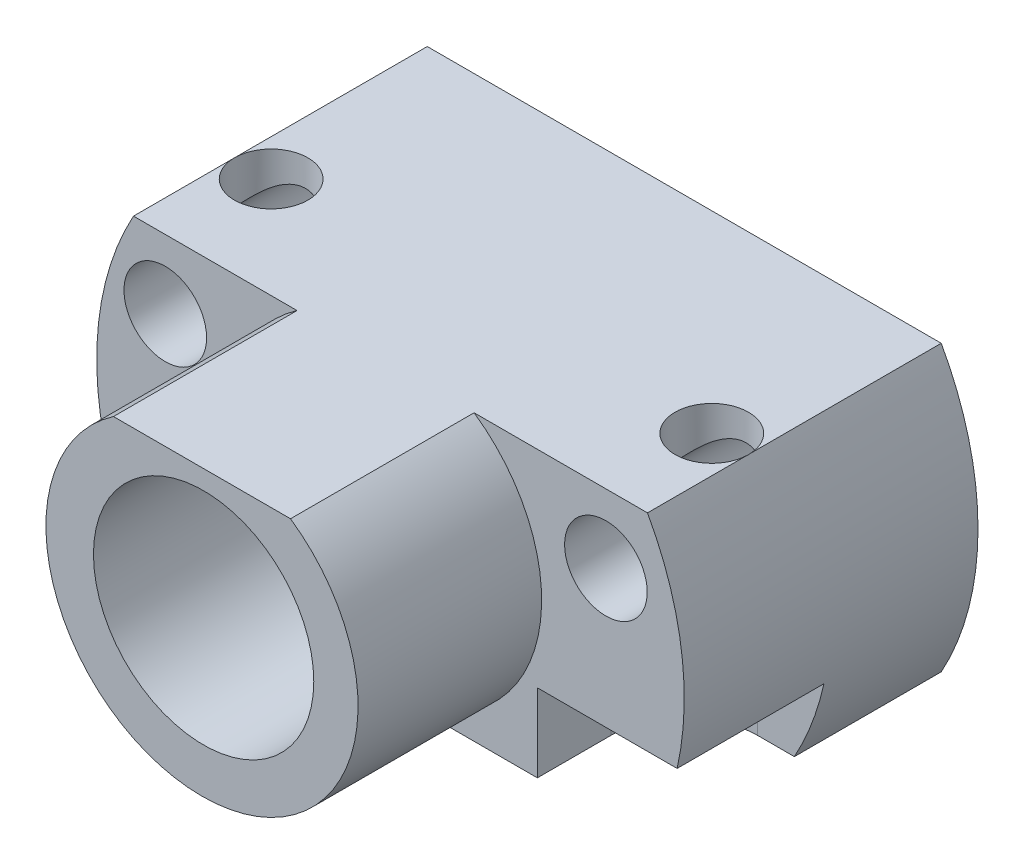
SolidWorks part; units mm, degrees
ref_plane "Plan de face" through (0, 0, 0) normal (0, 0, 1) x (1, 0, 0)
ref_plane "Plan de dessus" through (0, 0, 0) normal (0, 1, 0) x (1, 0, 0)
ref_plane "Plan de droite" through (0, 0, 0) normal (1, 0, 0) x (0, 0, -1)
sketch "Esquisse1" plane through (0, 0, 0) normal (0, 0, 1) x (1, 0, 0)
  line L1 (-27.4613, 12.1711) -> (28.5298, 12.1711)
  line L3 (-27.4613, -18.8289) -> (28.5298, -18.8289)
  arc A0 (-27.4613, 12.1711) -> (-27.4613, -18.8289) centre (0.5343, -3.3289) ccw
  arc A1 (28.5298, -18.8289) -> (28.5298, 12.1711) centre (0.5343, -3.3289) ccw
  dimension "D1" = 31
extrude "Boss.-Extru.1" add sketch "Esquisse1" along normal blind 32 contours A0 L3 A1 L1
sketch "Esquisse2" plane through (0, -18.8289, 0) normal (0, -1, 0) x (1, 0, 0)
  line L0 (0.5343, 32) -> (0.5343, -62.2542) construction
  line L1 (-27.4613, 0) -> (28.5298, 0) construction
  circle A0 centre (24.5343, 21) radius 4
  circle A1 centre (-23.4657, 21) radius 4
  dimension "D1" = 24
  dimension "D3" = 8
  dimension "D2" = 21
extrude "Enlèv. mat.-Extru.1" cut sketch "Esquisse2" against normal blind 32
sketch "Esquisse3" plane through (0, 0, 0) normal (0, 0, 1) x (1, 0, 0)
  line L0 (-27.4613, 12.1711) -> (28.5298, 12.1711) construction
  line L1 (0, 0) -> (0, 50000) construction
  circle A0 centre (-24, 4.6711) radius 4.5
  circle A1 centre (24, 4.6711) radius 4.5
  dimension "D1" = 7.5
  dimension "D2" = 24
extrude "Enlèv. mat.-Extru.3" cut sketch "Esquisse3" along normal blind 42
sketch "Esquisse4" [suppressed] plane through (0, 0, 0) normal (0, 1, 0) x (1, 0, 0)
  line L0 (16.5343, -32) -> (16.5343, -24)
  line L1 (-27.4613, -32) -> (28.5298, -32) construction
  line L2 (32.5343, -32) -> (32.5343, 0) construction
  line L3 (32.5343, -16) -> (24.5343, -16)
  line L4 (28.5298, -32) -> (32.5343, -32) construction
  line L5 (0.5343, -32) -> (0.5343, 49968) construction
  line L6 (-31.4657, -16) -> (-23.4657, -16)
  line L7 (-15.4657, -32) -> (-15.4657, -24)
  line L8 (32.5343, -16) -> (32.5343, -32)
  line L9 (32.5343, -32) -> (16.5343, -32)
  line L10 (-15.4657, -32) -> (-31.4657, -32)
  line L11 (-31.4657, -32) -> (-31.4657, -16)
  arc A0 (16.5343, -24) -> (24.5343, -16) centre (24.5343, -24) cw
  arc A1 (-15.4657, -24) -> (-23.4657, -16) centre (-23.4657, -24) ccw
  point P13 (0.5343, -32)
  point P19 (0, 0)
  point P24 (-15.4657, -24)
  dimension "D1" = 8
  dimension "D2" = 16
  dimension "D3" = 16
sketch "Esquisse5" plane through (0, -18.8289, 0) normal (0, -1, 0) x (1, 0, 0)
  line L0 (-15.4657, 32) -> (-15.4657, 24)
  line L1 (-27.4613, 32) -> (28.5298, 32) construction
  line L2 (-23.4657, 16) -> (-31.4657, 16)
  line L3 (-31.4657, 32) -> (-31.4657, 0) construction
  line L4 (-31.4657, 16) -> (-31.4657, 32)
  line L5 (-31.4657, 32) -> (-15.4657, 32)
  line L6 (0.5343, 32) -> (0.5343, -49968) construction
  line L7 (24.5343, 16) -> (32.5343, 16)
  line L8 (32.5343, 16) -> (32.5343, 32)
  line L9 (32.5343, 32) -> (16.5343, 32)
  line L10 (16.5343, 32) -> (16.5343, 24)
  arc A0 (-15.4657, 24) -> (-23.4657, 16) centre (-23.4657, 24) cw
  arc A1 (16.5343, 24) -> (24.5343, 16) centre (24.5343, 24) ccw
  point P10 (-15.4657, 16)
  point P13 (0.5343, 32)
  dimension "D3" = 8
  dimension "D1" = 16
  dimension "D2" = 16
extrude "Enlèv. mat.-Extru.4" cut sketch "Esquisse5" against normal blind 8.5
sketch "Esquisse6" plane through (0, 0, 32) normal (0, 0, 1) x (1, 0, 0)
  line L0 (0, -1.8289) -> (0, 12.1711) construction
  line L1 (-27.4613, 12.1711) -> (28.5298, 12.1711) construction
  line L2 (-9.6437, 12.1711) -> (9.6437, 12.1711)
  circle A0 centre (0, -1.8289) radius 17
  point P5 (0, 0)
  dimension "D1" = 14
extrude "Boss.-Extru.2" add sketch "Esquisse6" along normal blind 20
sketch "Esquisse7" plane through (0, 0, 52) normal (0, 0, 1) x (1, 0, 0)
  line L0 (-16.6744, -5.14) -> (8.856, -16.3399) construction
  line L1 (12.394, -13.4645) -> (16.8914, -3.7472) construction
  line L2 (14.6427, -8.6059) -> (-2.2027, -0.8094) construction
  line L3 (-3.9092, -10.74) -> (0.1771, -1.9108) construction
  arc A0 (-9.6437, 12.1711) -> (0, -18.8289) centre (0, -1.8289) ccw construction
  arc A1 (-9.6437, 12.1711) -> (9.6437, 12.1711) centre (0, -1.8289) ccw construction
  arc A2 (0, -18.8289) -> (9.6437, 12.1711) centre (0, -1.8289) ccw construction
  circle A3 centre (0.1771, -1.9108) radius 12
extrude "Enlèv. mat.-Extru.5" cut sketch "Esquisse7" against normal blind 33
